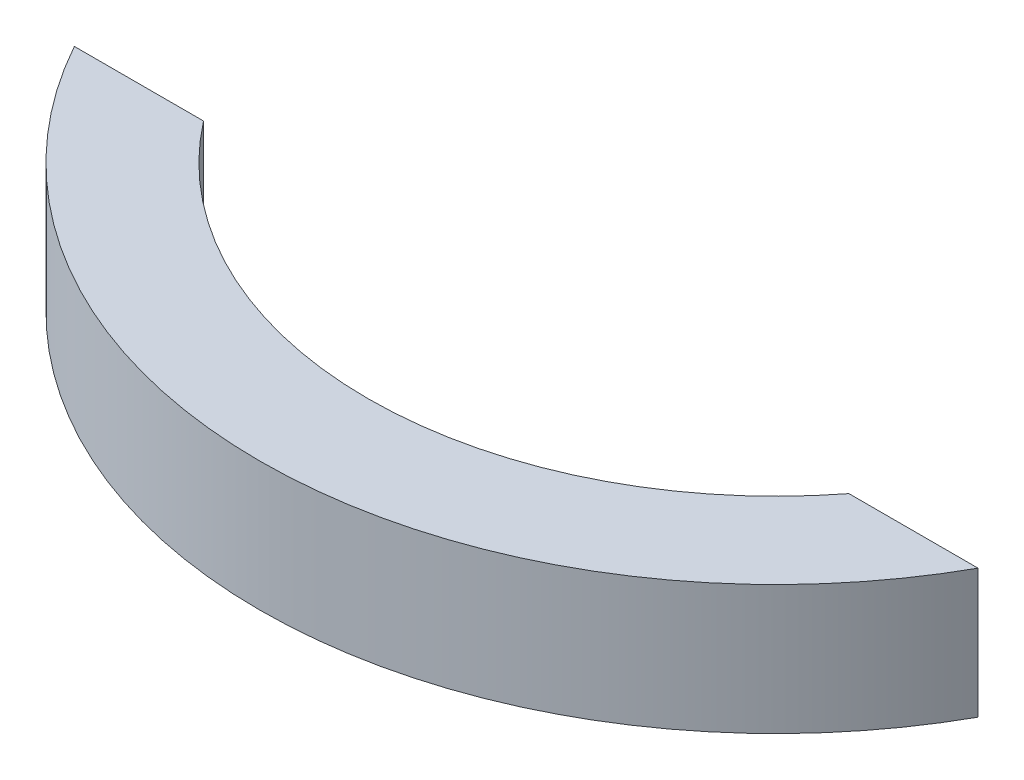
SolidWorks part; units mm, degrees
ref_plane "Front" through (0, 0, 0) normal (0, 0, 1) x (1, 0, 0)
ref_plane "Top" through (0, 0, 0) normal (0, 1, 0) x (1, 0, 0)
ref_plane "Right" through (0, 0, 0) normal (1, 0, 0) x (0, 0, -1)
sketch "Sketch1" plane through (0, 0, 0) normal (0, 1, 0) x (1, 0, 0)
  line L2 (-17.5, 5.3175) -> (-12.5, 5.3175)
  line L3 (12.5, 5.3175) -> (17.5, 5.3175)
  arc A2 (-17.5, 5.3175) -> (17.5, 5.3175) centre (0, 15) ccw
  arc A3 (-12.5, 5.3175) -> (12.5, 5.3175) centre (0, 15) ccw
  point P7 (0, -0.8114)
  dimension "D1" = 35
  dimension "D2" = 20
  dimension "D4" = 5
  dimension "D3" = 15
extrude "Boss-Extrude1" add sketch "Sketch1" along normal blind 5 contours A2 L3 A3 L2
